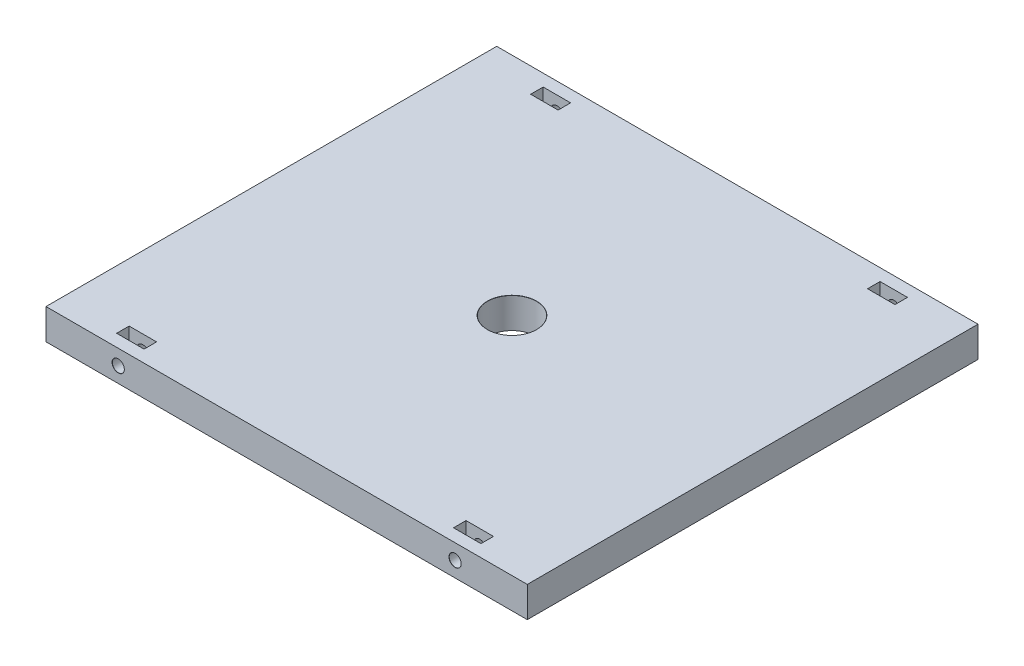
SolidWorks part; units mm, degrees
material "6061 Alloy"
ref_plane "Front Plane" through (0, 0, 0) normal (0, 0, 1) x (1, 0, 0)
ref_plane "Top Plane" through (0, 0, 0) normal (0, 1, 0) x (1, 0, 0)
ref_plane "Right Plane" through (0, 0, 0) normal (1, 0, 0) x (0, 0, -1)
sketch "Sketch1" plane through (0, 0, 0) normal (0, 1, 0) x (1, 0, 0)
  line L1 (-50, -46.825) -> (50, -46.825)
  line L2 (-50, -46.825) -> (-50, 46.825)
  line L3 (-50, 46.825) -> (50, 46.825)
  line L4 (50, -46.825) -> (50, 46.825)
  line L5 (-50, -46.825) -> (50, 46.825) construction
  line L6 (-50, 46.825) -> (50, -46.825) construction
  point P0 (0, 0)
extrude "Boss-Extrude1" add sketch "Sketch1" along normal blind 6.35
sketch "Sketch2" plane through (0, 0, 46.825) normal (0, 0, 1) x (1, 0, 0)
  line L0 (-50, 3.175) -> (-35, 3.175)
  line L1 (-50, 6.35) -> (-50, 0) construction
  line L2 (50, 3.175) -> (35, 3.175)
  line L3 (50, 6.35) -> (50, 0) construction
hole_wizard "Tap Drill for M3x0.5 Tap1" positions "Sketch3" profile "Sketch4" hole size "M3x0.5" standard "ANSI Metric"
sketch "Sketch3" plane through (0, 0, 46.825) normal (0, 0, 1) x (1, 0, 0)
  point P0 (-35, 3.175)
  point P3 (35, 3.175)
sketch "Sketch4" plane through (-35, 3.175, 46.825) normal (1, 0, 0) x (0, -1, 0)
  line L0 (0, 0) -> (0, 10)
  line L1 (0, 10) -> (1.25, 9.2489)
  line L2 (1.25, 9.2489) -> (1.25, 0.025)
  line L3 (1.25, 0.025) -> (1.275, 0)
  line L5 (1.275, 0) -> (0, 0)
  line L6 (-1.25, 0.025) -> (-1.275, 0) construction
  line L10 (0, 10) -> (-1.25, 9.2489) construction
  line L11 (0, -6.35) -> (0, 107.95) construction
  dimension "Hole Dia." = 2.5
  dimension "Hole Depth" = 10
  dimension "Near C'Sink Dia." = 2.55
  dimension "Near C'Sink Angle" = 90
  dimension "Drill Angle" = 118
sketch "Sketch5" plane through (0, 0, -46.825) normal (0, 0, -1) x (-1, 0, 0)
  line L0 (-50, 3.175) -> (-35, 3.175)
  line L1 (50, 3.175) -> (35, 3.175)
hole_wizard "Tap Drill for M3x0.5 Tap2" positions "Sketch6" profile "Sketch7" hole size "M3x0.5" standard "ANSI Metric"
sketch "Sketch6" plane through (0, 0, -46.825) normal (0, 0, -1) x (-1, 0, 0)
  point P0 (-35, 3.175)
  point P3 (35, 3.175)
sketch "Sketch7" plane through (35, 3.175, -46.825) normal (1, 0, 0) x (0, 1, 0)
  line L0 (0, 0) -> (0, 10)
  line L1 (0, 10) -> (1.25, 9.2489)
  line L2 (1.25, 9.2489) -> (1.25, 0.025)
  line L3 (1.25, 0.025) -> (1.275, 0)
  line L5 (1.275, 0) -> (0, 0)
  line L6 (-1.25, 0.025) -> (-1.275, 0) construction
  line L10 (0, 10) -> (-1.25, 9.2489) construction
  line L11 (0, -6.35) -> (0, 107.95) construction
  dimension "Hole Dia." = 2.5
  dimension "Hole Depth" = 10
  dimension "Near C'Sink Dia." = 2.55
  dimension "Near C'Sink Angle" = 90
  dimension "Drill Angle" = 118
hole_wizard "Tap Drill for M12x1.75 Tap1" positions "Sketch9" profile "Sketch10" hole size "M12x1.75" standard "ANSI Metric" end condition through all
sketch "Sketch9" plane through (0, 6.35, 0) normal (0, 1, 0) x (1, 0, 0)
  point P0 (0, 0)
sketch "Sketch10" plane through (0, 6.35, 0) normal (1, 0, 0) x (0, 0, 1)
  line L0 (0, 0) -> (0, 6.35)
  line L1 (0, 6.35) -> (5.1, 6.35)
  line L2 (5.1, 6.35) -> (5.1, 0.025)
  line L3 (5.1, 0.025) -> (5.125, 0)
  line L5 (5.125, 0) -> (0, 0)
  line L6 (-5.1, 0.025) -> (-5.125, 0) construction
  line L11 (0, -6.35) -> (0, 107.95) construction
  dimension "Thru Hole Dia." = 10.2
  dimension "Thru Hole Depth" = 6.35
  dimension "Near C'Sink Dia." = 10.25
  dimension "Near C'Sink Angle" = 90
sketch "Sketch11" plane through (0, 6.35, 0) normal (0, 1, 0) x (1, 0, 0)
  line L0 (33.75, 46.8) -> (36.25, 46.8) construction
  line L1 (-33.725, 46.825) -> (-36.275, 46.825) construction
  line L2 (36.25, -46.8) -> (33.75, -46.8) construction
  line L3 (-33.75, -46.8) -> (-36.25, -46.8) construction
  line L4 (33.75, 46.8) -> (36.25, 46.8) construction
  line L5 (-33.725, 46.825) -> (-36.275, 46.825) construction
  line L6 (36.25, -46.8) -> (33.75, -46.8) construction
  line L7 (-33.75, -46.8) -> (-36.25, -46.8) construction
  line L9 (32.15, -44.3) -> (37.85, -44.3)
  line L10 (32.15, -44.3) -> (32.15, -41.7)
  line L11 (32.15, -41.7) -> (37.85, -41.7)
  line L12 (37.85, -44.3) -> (37.85, -41.7)
  line L13 (32.15, -44.3) -> (37.85, -41.7) construction
  line L14 (32.15, -41.7) -> (37.85, -44.3) construction
  line L15 (-37.85, -44.3) -> (-32.15, -44.3)
  line L16 (-37.85, -44.3) -> (-37.85, -41.7)
  line L17 (-37.85, -41.7) -> (-32.15, -41.7)
  line L18 (-32.15, -44.3) -> (-32.15, -41.7)
  line L19 (-37.85, -44.3) -> (-32.15, -41.7) construction
  line L20 (-37.85, -41.7) -> (-32.15, -44.3) construction
  line L21 (-37.85, 44.325) -> (-32.15, 44.325)
  line L22 (-37.85, 44.325) -> (-37.85, 41.725)
  line L23 (-37.85, 41.725) -> (-32.15, 41.725)
  line L24 (-32.15, 44.325) -> (-32.15, 41.725)
  line L25 (-37.85, 44.325) -> (-32.15, 41.725) construction
  line L26 (-37.85, 41.725) -> (-32.15, 44.325) construction
  line L27 (32.15, 44.325) -> (37.85, 44.325)
  line L28 (32.15, 44.325) -> (32.15, 41.725)
  line L29 (32.15, 41.725) -> (37.85, 41.725)
  line L30 (37.85, 44.325) -> (37.85, 41.725)
  line L31 (32.15, 44.325) -> (37.85, 41.725) construction
  line L32 (32.15, 41.725) -> (37.85, 44.325) construction
  point P8 (35, -43)
  point P13 (-35, -43)
  point P18 (-35, 43.025)
  point P23 (35, 43.025)
  point P28 (0, 0)
  point P29 (-35, 46.825)
  point P30 (-35, -46.8)
  point P31 (35, -46.8)
  point P32 (35, 46.8)
  point P33 (-35, -44.3)
  point P34 (0, 0)
  point P35 (0, 0)
  dimension "D1" = 2.5
  dimension "D2" = 2.5
  dimension "D3" = 5.7
  dimension "D4" = 2.6
extrude "Cut-Extrude1" cut sketch "Sketch11" against normal through all
